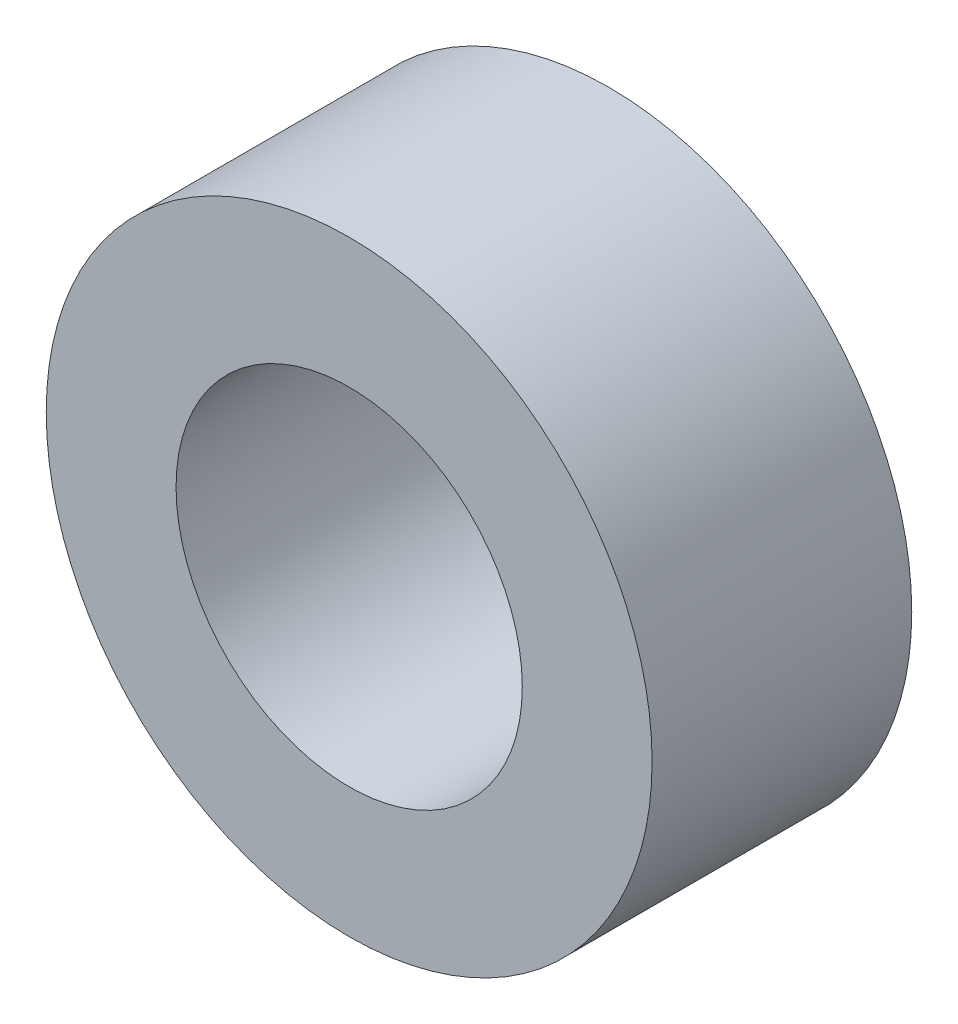
SolidWorks part; units mm, degrees
ref_plane "Front Plane" through (0, 0, 0) normal (0, 0, 1) x (1, 0, 0)
ref_plane "Top Plane" through (0, 0, 0) normal (0, 1, 0) x (1, 0, 0)
ref_plane "Right Plane" through (0, 0, 0) normal (1, 0, 0) x (0, 0, -1)
sketch "Sketch1" plane through (0, 0, 0) normal (0, 0, 1) x (1, 0, 0)
  circle A0 centre (0, 0) radius 3.5
  circle A1 centre (0, 0) radius 2
  dimension "D1" = 7
  dimension "D2" = 4
extrude "Boss-Extrude1" add sketch "Sketch1" along normal blind 3
